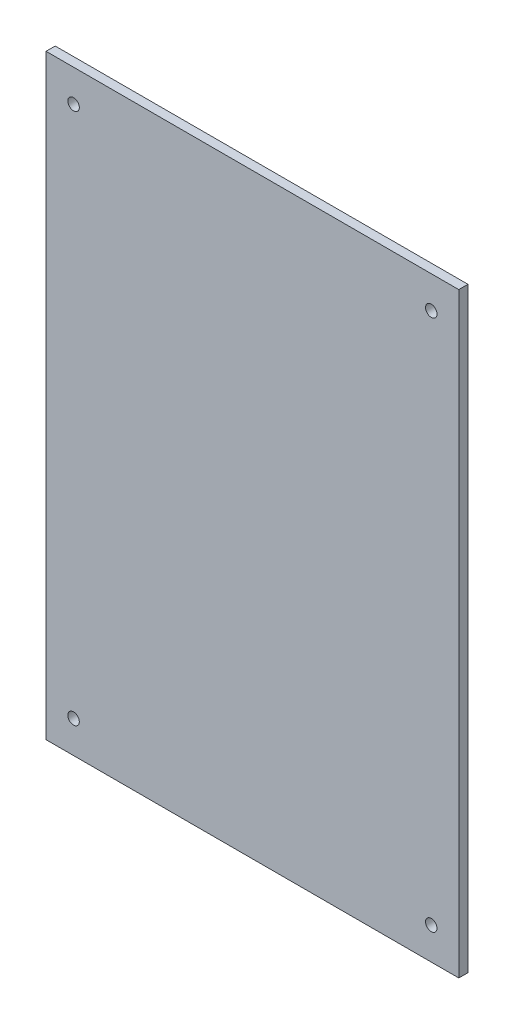
SolidWorks part; units mm, degrees
ref_plane "Front Plane" through (0, 0, 0) normal (0, 0, 1) x (1, 0, 0)
ref_plane "Top Plane" through (0, 0, 0) normal (0, 1, 0) x (1, 0, 0)
ref_plane "Right Plane" through (0, 0, 0) normal (1, 0, 0) x (0, 0, -1)
sketch "Sketch1" plane through (0, 0, 0) normal (0, 0, 1) x (1, 0, 0)
  line L1 (0, 0) -> (180, 0)
  line L2 (0, 0) -> (0, 260)
  line L3 (0, 260) -> (180, 260)
  line L4 (180, 0) -> (180, 260)
  circle A0 centre (12, 14) radius 2.5
  circle A1 centre (12, 246) radius 2.5
  circle A2 centre (168, 14) radius 2.5
  circle A3 centre (168, 246) radius 2.5
  dimension "D1" = 5
  dimension "D2" = 12
  dimension "D3" = 168
  dimension "D4" = 180
  dimension "D5" = 14
  dimension "D6" = 246
  dimension "D7" = 260
extrude "Profile" add sketch "Sketch1" along normal blind 4
equation "\"Profile_Depth\" = 4mm"
equation "\"D1@Profile\" = \"Profile_Depth\""
equation "\"Profile_Sketch_1\" = 5mm"
equation "\"D1@Sketch1\" = \"Profile_Sketch_1\""
equation "\"Profile_Sketch_2\" = 12mm"
equation "\"D2@Sketch1\" = \"Profile_Sketch_2\""
equation "\"Profile_Sketch_3\" = 168mm"
equation "\"D3@Sketch1\" = \"Profile_Sketch_3\""
equation "\"Profile_Sketch_4\" = 180mm"
equation "\"D4@Sketch1\" = \"Profile_Sketch_4\""
equation "\"Profile_Sketch_5\" = 14mm"
equation "\"D5@Sketch1\" = \"Profile_Sketch_5\""
equation "\"Profile_Sketch_6\" = 246mm"
equation "\"D6@Sketch1\" = \"Profile_Sketch_6\""
equation "\"Profile_Sketch_7\" = 260mm"
equation "\"D7@Sketch1\" = \"Profile_Sketch_7\""
equation "\"EnvelopeWidth\" = 180mm"
equation "\"EnvelopeHeight\" = 260mm"
